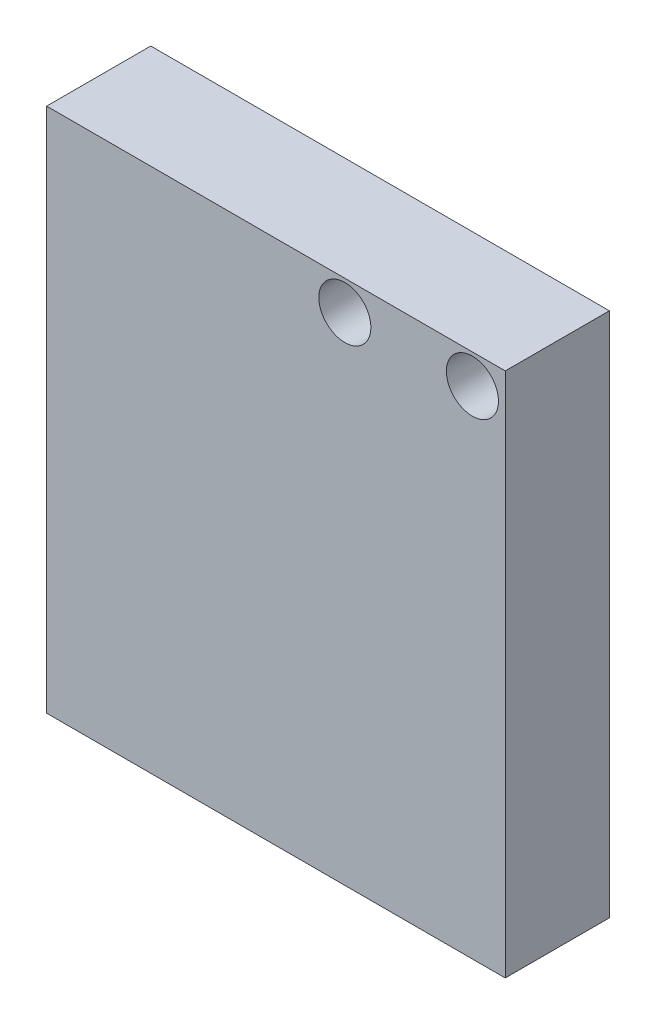
SolidWorks part; units mm, degrees
ref_plane "前视基准面" through (0, 0, 0) normal (0, 0, 1) x (1, 0, 0)
ref_plane "上视基准面" through (0, 0, 0) normal (0, 1, 0) x (1, 0, 0)
ref_plane "右视基准面" through (0, 0, 0) normal (1, 0, 0) x (0, 0, -1)
other "图形1"
other "图形 (打开) -1"
sketch "草图4" plane through (0, 0, 0) normal (0, 0, 1) x (1, 0, 0)
  line L1 (4062.092, -3176.1105) -> (4079.712, -3176.1105)
  line L2 (4062.092, -3176.1105) -> (4062.092, -3196.3103)
  line L3 (4062.092, -3196.3103) -> (4079.712, -3196.3103)
  line L4 (4079.712, -3176.1105) -> (4079.712, -3196.3103)
  circle A0 centre (4073.549, -3177.2491) radius 1
  circle A1 centre (4078.4499, -3177.2491) radius 1
  point P8 (0, 0)
  point P9 (4205.3019, -3279.9999)
  point P10 (4062.092, -3176.1105)
  point P11 (4079.712, -3196.3103)
  point P12 (4073.549, -3177.2491)
  point P13 (4078.442, -3177.2491)
  point P14 (4078.4499, -3177.2491)
  point P15 (0, 0)
  point P16 (0, 0)
  point P17 (0, 0)
  point P18 (0, 0)
  dimension "D1" = 2
  dimension "D2" = 1.1385
  dimension "D3" = 1.2621
  dimension "D4" = 4.9008
extrude "凸台-拉伸1" add sketch "草图4" along normal blind 4 from offset 6 contours L2 L3 L4 L1 | A0 | A1
